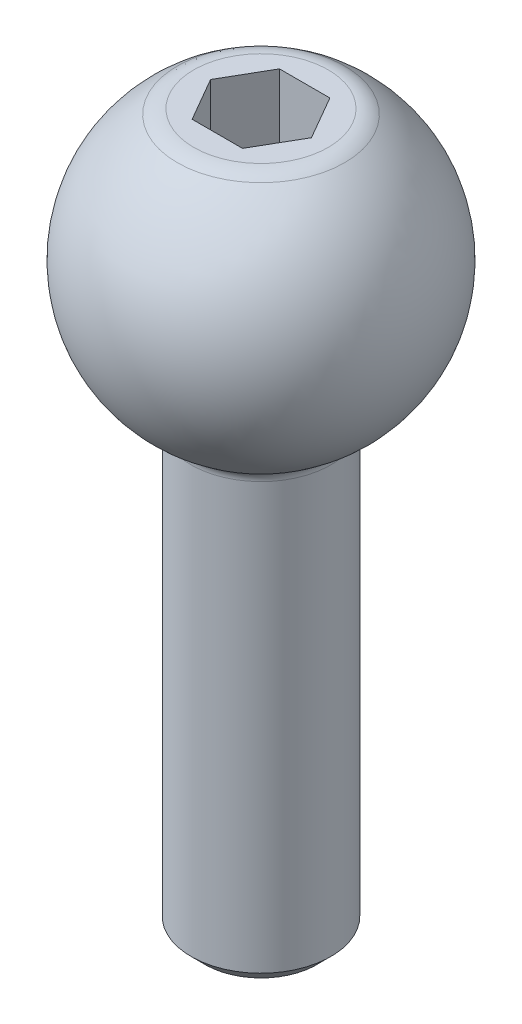
SolidWorks part; units mm, degrees
ref_plane "Front Plane" through (0, 0, 0) normal (0, 0, 1) x (1, 0, 0)
ref_plane "Top Plane" through (0, 0, 0) normal (0, 1, 0) x (1, 0, 0)
ref_plane "Right Plane" through (0, 0, 0) normal (1, 0, 0) x (0, 0, -1)
sketch "Sketch1" plane through (0, 0, 0) normal (0, 0, 1) x (1, 0, 0)
  line L0 (0, -648.6344) -> (0, 31783.0857) construction
  line L1 (0, -15.875) -> (-1.905, -15.875)
  line L2 (-1.905, -15.875) -> (-1.905, -3.6616)
  line L3 (0, 4.1275) -> (0, -15.875)
  arc A1 (0, 4.1275) -> (-1.905, -3.6616) centre (0, 0) ccw
  dimension "D1" = 4.1275
  dimension "D2" = 3.81
  dimension "D3" = 15.875
revolve "Revolve1" add sketch "Sketch1" angle 360 about L0
cosmetic thread "Cosmetic Thread1" parameters "D2"=2.7483
fillet "Fillet1" radius 0.381 1 edges at (1.905, -3.6616, 0)
chamfer "Chamfer1" distance 0.381 1 edges at (1.905, -15.875, 0)
sketch "Sketch2" plane through (0, 0, 0) normal (0, 0, 1) x (1, 0, 0)
  line L0 (1.905, -15.494) -> (1.524, -15.875)
  line L1 (-1.524, -15.875) -> (-1.905, -15.494)
  line L2 (-1.524, -15.875) -> (1.524, -15.875)
  line L3 (-1.905, -3.886) -> (-1.905, -15.494)
  line L4 (1.905, -15.494) -> (1.905, -3.886)
  line L5 (1.905, -15.494) -> (1.905, -3.886) construction
  line L6 (-1.905, -3.886) -> (-1.905, -15.494) construction
  line L7 (-1.524, -15.875) -> (1.524, -15.875) construction
  line L8 (-1.524, -15.875) -> (-1.905, -15.494) construction
  line L9 (1.905, -15.494) -> (1.524, -15.875) construction
  line L10 (-2.0638, 3.5745) -> (2.0638, 3.5745)
  arc A0 (2.0928, -3.5576) -> (1.905, -3.886) centre (2.286, -3.886) ccw
  arc A1 (-1.905, -3.886) -> (-2.0928, -3.5576) centre (-2.286, -3.886) ccw
  arc A2 (2.0928, -3.5576) -> (-2.0928, -3.5576) centre (0, 0) ccw
  arc A3 (2.0928, -3.5576) -> (-2.0928, -3.5576) centre (0, 0) ccw construction
  arc A4 (-1.905, -3.886) -> (-2.0928, -3.5576) centre (-2.286, -3.886) ccw construction
  arc A5 (2.0928, -3.5576) -> (1.905, -3.886) centre (2.286, -3.886) ccw
  dimension "D1" = 4.1275
ref_plane "Plane1" through (0, 3.5745, 0) normal (0, 1, 0) x (1, 0, 0)
split "Split1" trim tools "Plane1" bodies to split 101 resulting bodies 102
fillet "Fillet2" radius 0.8128 1 edges at (0, 3.5745, 2.0638)
sketch "Sketch3" plane through (0, 3.5745, 0) normal (0, 1, 0) x (1, 0, 0)
  line L1 (0.6874, 1.1906) -> (-0.6874, 1.1906)
  line L2 (-0.6874, 1.1906) -> (-1.3748, 0)
  line L3 (-1.3748, 0) -> (-0.6874, -1.1906)
  line L4 (-0.6874, -1.1906) -> (0.6874, -1.1906)
  line L5 (0.6874, -1.1906) -> (1.3748, 0)
  line L6 (1.3748, 0) -> (0.6874, 1.1906)
  circle A0 centre (0, 0) radius 1.1906 construction
  dimension "D1" = 2.3813
extrude "Cut-Extrude1" cut sketch "Sketch3" against normal blind 2.54
